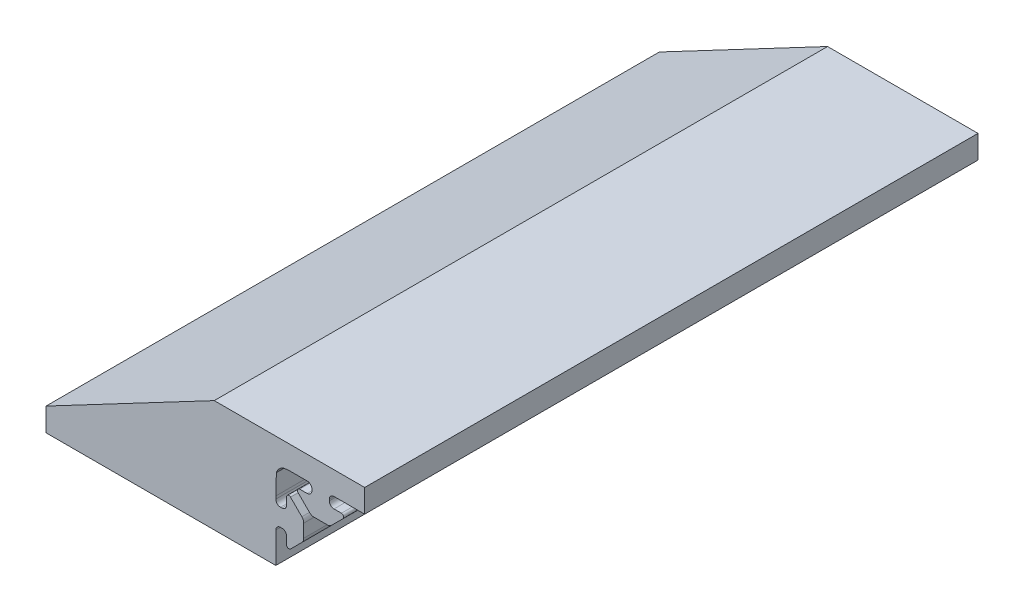
SolidWorks part; units mm, degrees
ref_plane "Front Plane" through (0, 0, 0) normal (0, 0, 1) x (1, 0, 0)
ref_plane "Top Plane" through (0, 0, 0) normal (0, 1, 0) x (1, 0, 0)
ref_plane "Right Plane" through (0, 0, 0) normal (1, 0, 0) x (0, 0, -1)
sketch "Sketch1" plane through (0, 0, 0) normal (0, 0, 1) x (1, 0, 0)
  line L6 (-87.85, -284.05) -> (-19.05, -284.05)
  line L7 (-19.05, -284.05) -> (-19.05, -269.05)
  line L8 (-19.05, -269.05) -> (-118.6495, -269.05)
  line L9 (-118.6495, -269.05) -> (-118.6495, -295.05)
  line L10 (-118.6495, -295.05) -> (-87.85, -295.05)
  line L11 (-87.85, -295.05) -> (-87.85, -284.05)
  line L12 (-87.85, -284.05) -> (-19.05, -284.05)
  line L13 (-19.05, -284.05) -> (-19.05, -269.05)
  line L14 (-19.05, -269.05) -> (-118.6495, -269.05)
  line L15 (-118.6495, -269.05) -> (-118.6495, -295.05)
  line L16 (-118.6495, -295.05) -> (-87.85, -295.05)
  line L17 (-87.85, -295.05) -> (-87.85, -284.05)
  line L44 (19.05, -6.9643) -> (19.05, -5.7912)
  line L45 (17.3228, -4.064) -> (16.7132, -4.064)
  line L46 (14.986, -5.7912) -> (14.986, -8.9963)
  line L47 (12.7826, -9.909) -> (7.8889, -5.0152)
  line L48 (6.985, -2.833) -> (6.985, 2.833)
  line L49 (7.8889, 5.0152) -> (12.7826, 9.909)
  line L50 (14.986, 8.9963) -> (14.986, 5.7912)
  line L51 (16.7132, 4.064) -> (17.3228, 4.064)
  line L52 (19.05, 5.7912) -> (19.05, 6.9643)
  line L53 (19.05, 8.9963) -> (19.05, 13.7235)
  line L54 (13.7235, 19.05) -> (8.9963, 19.05)
  line L55 (6.9643, 19.05) -> (5.7912, 19.05)
  line L56 (4.064, 17.3228) -> (4.064, 16.7132)
  line L57 (5.7912, 14.986) -> (8.9963, 14.986)
  line L58 (9.909, 12.7826) -> (5.0152, 7.8889)
  line L59 (2.833, 6.985) -> (-2.833, 6.985)
  line L60 (-5.0152, 7.8889) -> (-9.909, 12.7826)
  line L61 (-8.9963, 14.986) -> (-5.7912, 14.986)
  line L62 (-4.064, 16.7132) -> (-4.064, 17.3228)
  line L63 (-5.7912, 19.05) -> (-6.9643, 19.05)
  line L64 (-8.9963, 19.05) -> (-13.7235, 19.05)
  line L65 (-19.05, 13.7235) -> (-19.05, 8.9963)
  line L66 (-19.05, 6.9643) -> (-19.05, 5.7912)
  line L67 (-17.3228, 4.064) -> (-16.7132, 4.064)
  line L68 (-14.986, 5.7912) -> (-14.986, 8.9963)
  line L69 (-12.7826, 9.909) -> (-7.8889, 5.0152)
  line L70 (-6.985, 2.833) -> (-6.985, -2.833)
  line L71 (-7.8889, -5.0152) -> (-12.7826, -9.909)
  line L72 (-14.986, -8.9963) -> (-14.986, -5.7912)
  line L73 (-16.7132, -4.064) -> (-17.3228, -4.064)
  line L74 (-19.05, -5.7912) -> (-19.05, -6.9643)
  line L75 (-19.05, -8.9963) -> (-19.05, -13.7235)
  line L76 (-13.7235, -19.05) -> (-8.9963, -19.05)
  line L77 (-6.9643, -19.05) -> (-5.7912, -19.05)
  line L78 (-4.064, -17.3228) -> (-4.064, -16.7132)
  line L79 (-5.7912, -14.986) -> (-8.9963, -14.986)
  line L80 (-9.909, -12.7826) -> (-5.0152, -7.8889)
  line L81 (-2.833, -6.985) -> (2.833, -6.985)
  line L82 (5.0152, -7.8889) -> (9.909, -12.7826)
  line L83 (8.9963, -14.986) -> (5.7912, -14.986)
  line L84 (4.064, -16.7132) -> (4.064, -17.3228)
  line L85 (5.7912, -19.05) -> (6.9643, -19.05)
  line L86 (8.9963, -19.05) -> (13.7235, -19.05)
  line L87 (19.05, -13.7235) -> (19.05, -8.9963)
  line L88 (19.05, -6.9643) -> (19.05, -5.7912)
  line L89 (17.3228, -4.064) -> (16.7132, -4.064)
  line L90 (14.986, -5.7912) -> (14.986, -8.9963)
  line L91 (12.7826, -9.909) -> (7.8889, -5.0152)
  line L92 (6.985, -2.833) -> (6.985, 2.833)
  line L93 (7.8889, 5.0152) -> (12.7826, 9.909)
  line L94 (14.986, 8.9963) -> (14.986, 5.7912)
  line L95 (16.7132, 4.064) -> (17.3228, 4.064)
  line L96 (19.05, 5.7912) -> (19.05, 6.9643)
  line L97 (19.05, 8.9963) -> (19.05, 13.7235)
  line L98 (13.7235, 19.05) -> (8.9963, 19.05)
  line L99 (6.9643, 19.05) -> (5.7912, 19.05)
  line L100 (4.064, 17.3228) -> (4.064, 16.7132)
  line L101 (5.7912, 14.986) -> (8.9963, 14.986)
  line L102 (9.909, 12.7826) -> (5.0152, 7.8889)
  line L103 (2.833, 6.985) -> (-2.833, 6.985)
  line L104 (-5.0152, 7.8889) -> (-9.909, 12.7826)
  line L105 (-8.9963, 14.986) -> (-5.7912, 14.986)
  line L106 (-4.064, 16.7132) -> (-4.064, 17.3228)
  line L107 (-5.7912, 19.05) -> (-6.9643, 19.05)
  line L108 (-8.9963, 19.05) -> (-13.7235, 19.05)
  line L109 (-19.05, 13.7235) -> (-19.05, 8.9963)
  line L110 (-19.05, 6.9643) -> (-19.05, 5.7912)
  line L111 (-17.3228, 4.064) -> (-16.7132, 4.064)
  line L112 (-14.986, 5.7912) -> (-14.986, 8.9963)
  line L113 (-12.7826, 9.909) -> (-7.8889, 5.0152)
  line L114 (-6.985, 2.833) -> (-6.985, -2.833)
  line L115 (-7.8889, -5.0152) -> (-12.7826, -9.909)
  line L116 (-14.986, -8.9963) -> (-14.986, -5.7912)
  line L117 (-16.7132, -4.064) -> (-17.3228, -4.064)
  line L118 (-19.05, -5.7912) -> (-19.05, -6.9643)
  line L119 (-19.05, -8.9963) -> (-19.05, -13.7235)
  line L120 (-13.7235, -19.05) -> (-8.9963, -19.05)
  line L121 (-6.9643, -19.05) -> (-5.7912, -19.05)
  line L122 (-4.064, -17.3228) -> (-4.064, -16.7132)
  line L123 (-5.7912, -14.986) -> (-8.9963, -14.986)
  line L124 (-9.909, -12.7826) -> (-5.0152, -7.8889)
  line L125 (-2.833, -6.985) -> (2.833, -6.985)
  line L126 (5.0152, -7.8889) -> (9.909, -12.7826)
  line L127 (8.9963, -14.986) -> (5.7912, -14.986)
  line L128 (4.064, -16.7132) -> (4.064, -17.3228)
  line L129 (5.7912, -19.05) -> (6.9643, -19.05)
  line L130 (8.9963, -19.05) -> (13.7235, -19.05)
  line L131 (19.05, -13.7235) -> (19.05, -8.9963)
  arc A52 (19.05, -6.9643) -> (19.05, -8.9963) centre (19.05, -7.9803) ccw
  arc A53 (19.05, -5.7912) -> (17.3228, -4.064) centre (17.3228, -5.7912) ccw
  arc A54 (16.7132, -4.064) -> (14.986, -5.7912) centre (16.7132, -5.7912) ccw
  arc A55 (12.7826, -9.909) -> (14.986, -8.9963) centre (13.6953, -8.9963) ccw
  arc A56 (6.985, -2.833) -> (7.8889, -5.0152) centre (10.0711, -2.833) ccw
  arc A57 (7.8889, 5.0152) -> (6.985, 2.833) centre (10.0711, 2.833) ccw
  arc A58 (14.986, 8.9963) -> (12.7826, 9.909) centre (13.6953, 8.9963) ccw
  arc A59 (14.986, 5.7912) -> (16.7132, 4.064) centre (16.7132, 5.7912) ccw
  arc A60 (17.3228, 4.064) -> (19.05, 5.7912) centre (17.3228, 5.7912) ccw
  arc A61 (19.05, 8.9963) -> (19.05, 6.9643) centre (19.05, 7.9803) ccw
  arc A62 (18.8293, 15.7312) -> (19.05, 13.7235) centre (19.05, 14.7395) ccw
  arc A63 (18.8293, 15.7312) -> (15.7312, 18.8293) centre (14.3002, 14.3002) ccw
  arc A64 (13.7235, 19.05) -> (15.7312, 18.8293) centre (14.7395, 19.05) ccw
  arc A65 (6.9643, 19.05) -> (8.9963, 19.05) centre (7.9803, 19.05) ccw
  arc A66 (5.7912, 19.05) -> (4.064, 17.3228) centre (5.7912, 17.3228) ccw
  arc A67 (4.064, 16.7132) -> (5.7912, 14.986) centre (5.7912, 16.7132) ccw
  arc A68 (9.909, 12.7826) -> (8.9963, 14.986) centre (8.9963, 13.6953) ccw
  arc A69 (2.833, 6.985) -> (5.0152, 7.8889) centre (2.833, 10.0711) ccw
  arc A70 (-5.0152, 7.8889) -> (-2.833, 6.985) centre (-2.833, 10.0711) ccw
  arc A71 (-8.9963, 14.986) -> (-9.909, 12.7826) centre (-8.9963, 13.6953) ccw
  arc A72 (-5.7912, 14.986) -> (-4.064, 16.7132) centre (-5.7912, 16.7132) ccw
  arc A73 (-4.064, 17.3228) -> (-5.7912, 19.05) centre (-5.7912, 17.3228) ccw
  arc A74 (-8.9963, 19.05) -> (-6.9643, 19.05) centre (-7.9803, 19.05) ccw
  arc A75 (-15.7312, 18.8293) -> (-13.7235, 19.05) centre (-14.7395, 19.05) ccw
  arc A76 (-15.7312, 18.8293) -> (-18.8293, 15.7312) centre (-14.3002, 14.3002) ccw
  arc A77 (-19.05, 13.7235) -> (-18.8293, 15.7312) centre (-19.05, 14.7395) ccw
  arc A78 (-19.05, 6.9643) -> (-19.05, 8.9963) centre (-19.05, 7.9803) ccw
  arc A79 (-19.05, 5.7912) -> (-17.3228, 4.064) centre (-17.3228, 5.7912) ccw
  arc A80 (-16.7132, 4.064) -> (-14.986, 5.7912) centre (-16.7132, 5.7912) ccw
  arc A81 (-12.7826, 9.909) -> (-14.986, 8.9963) centre (-13.6953, 8.9963) ccw
  arc A82 (-6.985, 2.833) -> (-7.8889, 5.0152) centre (-10.0711, 2.833) ccw
  arc A83 (-7.8889, -5.0152) -> (-6.985, -2.833) centre (-10.0711, -2.833) ccw
  arc A84 (-14.986, -8.9963) -> (-12.7826, -9.909) centre (-13.6953, -8.9963) ccw
  arc A85 (-14.986, -5.7912) -> (-16.7132, -4.064) centre (-16.7132, -5.7912) ccw
  arc A86 (-17.3228, -4.064) -> (-19.05, -5.7912) centre (-17.3228, -5.7912) ccw
  arc A87 (-19.05, -8.9963) -> (-19.05, -6.9643) centre (-19.05, -7.9803) ccw
  arc A88 (-18.8293, -15.7312) -> (-19.05, -13.7235) centre (-19.05, -14.7395) ccw
  arc A89 (-18.8293, -15.7312) -> (-15.7312, -18.8293) centre (-14.3002, -14.3002) ccw
  arc A90 (-13.7235, -19.05) -> (-15.7312, -18.8293) centre (-14.7395, -19.05) ccw
  arc A91 (-6.9643, -19.05) -> (-8.9963, -19.05) centre (-7.9803, -19.05) ccw
  arc A92 (-5.7912, -19.05) -> (-4.064, -17.3228) centre (-5.7912, -17.3228) ccw
  arc A93 (-4.064, -16.7132) -> (-5.7912, -14.986) centre (-5.7912, -16.7132) ccw
  arc A94 (-9.909, -12.7826) -> (-8.9963, -14.986) centre (-8.9963, -13.6953) ccw
  arc A95 (-2.833, -6.985) -> (-5.0152, -7.8889) centre (-2.833, -10.0711) ccw
  arc A96 (5.0152, -7.8889) -> (2.833, -6.985) centre (2.833, -10.0711) ccw
  arc A97 (8.9963, -14.986) -> (9.909, -12.7826) centre (8.9963, -13.6953) ccw
  arc A98 (5.7912, -14.986) -> (4.064, -16.7132) centre (5.7912, -16.7132) ccw
  arc A99 (4.064, -17.3228) -> (5.7912, -19.05) centre (5.7912, -17.3228) ccw
  arc A100 (8.9963, -19.05) -> (6.9643, -19.05) centre (7.9803, -19.05) ccw
  arc A101 (15.7312, -18.8293) -> (13.7235, -19.05) centre (14.7395, -19.05) ccw
  arc A102 (15.7312, -18.8293) -> (18.8293, -15.7312) centre (14.3002, -14.3002) ccw
  arc A103 (19.05, -13.7235) -> (18.8293, -15.7312) centre (19.05, -14.7395) ccw
  arc A104 (19.05, -6.9643) -> (19.05, -8.9963) centre (19.05, -7.9803) ccw
  arc A105 (19.05, -5.7912) -> (17.3228, -4.064) centre (17.3228, -5.7912) ccw
  arc A106 (16.7132, -4.064) -> (14.986, -5.7912) centre (16.7132, -5.7912) ccw
  arc A107 (12.7826, -9.909) -> (14.986, -8.9963) centre (13.6953, -8.9963) ccw
  arc A108 (6.985, -2.833) -> (7.8889, -5.0152) centre (10.0711, -2.833) ccw
  arc A109 (7.8889, 5.0152) -> (6.985, 2.833) centre (10.0711, 2.833) ccw
  arc A110 (14.986, 8.9963) -> (12.7826, 9.909) centre (13.6953, 8.9963) ccw
  arc A111 (14.986, 5.7912) -> (16.7132, 4.064) centre (16.7132, 5.7912) ccw
  arc A112 (17.3228, 4.064) -> (19.05, 5.7912) centre (17.3228, 5.7912) ccw
  arc A113 (19.05, 8.9963) -> (19.05, 6.9643) centre (19.05, 7.9803) ccw
  arc A114 (18.8293, 15.7312) -> (19.05, 13.7235) centre (19.05, 14.7395) ccw
  arc A115 (18.8293, 15.7312) -> (15.7312, 18.8293) centre (14.3002, 14.3002) ccw
  arc A116 (13.7235, 19.05) -> (15.7312, 18.8293) centre (14.7395, 19.05) ccw
  arc A117 (6.9643, 19.05) -> (8.9963, 19.05) centre (7.9803, 19.05) ccw
  arc A118 (5.7912, 19.05) -> (4.064, 17.3228) centre (5.7912, 17.3228) ccw
  arc A119 (4.064, 16.7132) -> (5.7912, 14.986) centre (5.7912, 16.7132) ccw
  arc A120 (9.909, 12.7826) -> (8.9963, 14.986) centre (8.9963, 13.6953) ccw
  arc A121 (2.833, 6.985) -> (5.0152, 7.8889) centre (2.833, 10.0711) ccw
  arc A122 (-5.0152, 7.8889) -> (-2.833, 6.985) centre (-2.833, 10.0711) ccw
  arc A123 (-8.9963, 14.986) -> (-9.909, 12.7826) centre (-8.9963, 13.6953) ccw
  arc A124 (-5.7912, 14.986) -> (-4.064, 16.7132) centre (-5.7912, 16.7132) ccw
  arc A125 (-4.064, 17.3228) -> (-5.7912, 19.05) centre (-5.7912, 17.3228) ccw
  arc A126 (-8.9963, 19.05) -> (-6.9643, 19.05) centre (-7.9803, 19.05) ccw
  arc A127 (-15.7312, 18.8293) -> (-13.7235, 19.05) centre (-14.7395, 19.05) ccw
  arc A128 (-15.7312, 18.8293) -> (-18.8293, 15.7312) centre (-14.3002, 14.3002) ccw
  arc A129 (-19.05, 13.7235) -> (-18.8293, 15.7312) centre (-19.05, 14.7395) ccw
  arc A130 (-19.05, 6.9643) -> (-19.05, 8.9963) centre (-19.05, 7.9803) ccw
  arc A131 (-19.05, 5.7912) -> (-17.3228, 4.064) centre (-17.3228, 5.7912) ccw
  arc A132 (-16.7132, 4.064) -> (-14.986, 5.7912) centre (-16.7132, 5.7912) ccw
  arc A133 (-12.7826, 9.909) -> (-14.986, 8.9963) centre (-13.6953, 8.9963) ccw
  arc A134 (-6.985, 2.833) -> (-7.8889, 5.0152) centre (-10.0711, 2.833) ccw
  arc A135 (-7.8889, -5.0152) -> (-6.985, -2.833) centre (-10.0711, -2.833) ccw
  arc A136 (-14.986, -8.9963) -> (-12.7826, -9.909) centre (-13.6953, -8.9963) ccw
  arc A137 (-14.986, -5.7912) -> (-16.7132, -4.064) centre (-16.7132, -5.7912) ccw
  arc A138 (-17.3228, -4.064) -> (-19.05, -5.7912) centre (-17.3228, -5.7912) ccw
  arc A139 (-19.05, -8.9963) -> (-19.05, -6.9643) centre (-19.05, -7.9803) ccw
  arc A140 (-18.8293, -15.7312) -> (-19.05, -13.7235) centre (-19.05, -14.7395) ccw
  arc A141 (-18.8293, -15.7312) -> (-15.7312, -18.8293) centre (-14.3002, -14.3002) ccw
  arc A142 (-13.7235, -19.05) -> (-15.7312, -18.8293) centre (-14.7395, -19.05) ccw
  arc A143 (-6.9643, -19.05) -> (-8.9963, -19.05) centre (-7.9803, -19.05) ccw
  arc A144 (-5.7912, -19.05) -> (-4.064, -17.3228) centre (-5.7912, -17.3228) ccw
  arc A145 (-4.064, -16.7132) -> (-5.7912, -14.986) centre (-5.7912, -16.7132) ccw
  arc A146 (-9.909, -12.7826) -> (-8.9963, -14.986) centre (-8.9963, -13.6953) ccw
  arc A147 (-2.833, -6.985) -> (-5.0152, -7.8889) centre (-2.833, -10.0711) ccw
  arc A148 (5.0152, -7.8889) -> (2.833, -6.985) centre (2.833, -10.0711) ccw
  arc A149 (8.9963, -14.986) -> (9.909, -12.7826) centre (8.9963, -13.6953) ccw
  arc A150 (5.7912, -14.986) -> (4.064, -16.7132) centre (5.7912, -16.7132) ccw
  arc A151 (4.064, -17.3228) -> (5.7912, -19.05) centre (5.7912, -17.3228) ccw
  arc A152 (8.9963, -19.05) -> (6.9643, -19.05) centre (7.9803, -19.05) ccw
  arc A153 (15.7312, -18.8293) -> (13.7235, -19.05) centre (14.7395, -19.05) ccw
  arc A154 (15.7312, -18.8293) -> (18.8293, -15.7312) centre (14.3002, -14.3002) ccw
  arc A155 (19.05, -13.7235) -> (18.8293, -15.7312) centre (19.05, -14.7395) ccw
  dimension "D1" = 0
  dimension "D2" = 0
sketch "Sketch2" plane through (0, 0, 0) normal (0, 0, 1) x (1, 0, 0)
  line L60 (-7.285, 2.833) -> (-7.285, -2.833)
  line L61 (-8.101, -4.8031) -> (-12.9948, -9.6968)
  line L62 (-14.686, -8.9963) -> (-14.686, -5.7912)
  line L63 (-16.7132, -3.764) -> (-17.3228, -3.764)
  line L64 (-17.3228, 3.764) -> (-16.7132, 3.764)
  line L65 (-14.686, 5.7912) -> (-14.686, 8.9963)
  line L66 (-12.9948, 9.6968) -> (-8.101, 4.8031)
  line L67 (-7.285, 2.833) -> (-7.285, -2.833)
  line L68 (-8.101, -4.8031) -> (-12.9948, -9.6968)
  line L69 (-14.686, -8.9963) -> (-14.686, -5.7912)
  line L70 (-16.7132, -3.764) -> (-17.3228, -3.764)
  line L71 (-17.3228, 3.764) -> (-16.7132, 3.764)
  line L72 (-14.686, 5.7912) -> (-14.686, 8.9963)
  line L73 (-12.9948, 9.6968) -> (-8.101, 4.8031)
  line L75 (-8.9963, 14.686) -> (-5.7912, 14.686)
  line L76 (-3.764, 16.7132) -> (-3.764, 17.3228)
  line L77 (-8.9963, 14.686) -> (-5.7912, 14.686)
  line L78 (-3.764, 16.7132) -> (-3.764, 17.3228)
  line L119 (6.9643, 19.35) -> (5.7912, 19.35)
  line L120 (3.764, 17.3228) -> (3.764, 16.7132)
  line L121 (5.7912, 14.686) -> (8.9963, 14.686)
  line L122 (9.6968, 12.9948) -> (4.8031, 8.101)
  line L123 (2.833, 7.285) -> (-2.833, 7.285)
  line L124 (-4.8031, 8.101) -> (-9.6968, 12.9948)
  line L125 (6.9643, 19.35) -> (5.7912, 19.35)
  line L126 (3.764, 17.3228) -> (3.764, 16.7132)
  line L127 (5.7912, 14.686) -> (8.9963, 14.686)
  line L128 (9.6968, 12.9948) -> (4.8031, 8.101)
  line L129 (2.833, 7.285) -> (-2.833, 7.285)
  line L130 (-4.8031, 8.101) -> (-9.6968, 12.9948)
  line L132 (-19.35, 6.9643) -> (-19.35, 5.7912)
  line L133 (-19.35, 6.9643) -> (-19.35, 5.7912)
  line L135 (-8.9963, 19.35) -> (-13.7235, 19.35)
  line L136 (-8.9963, 19.35) -> (-13.7235, 19.35)
  line L137 (-19.35, -6.9643) -> (-19.35, -19.05)
  line L138 (-19.35, -5.7912) -> (-19.35, -6.9643)
  line L139 (-19.35, -5.7912) -> (-19.35, -6.9643)
  line L140 (-19.35, 6.9643) -> (-19.1154, 15.8216)
  line L142 (-15.8216, 19.1154) -> (-13.7235, 19.35)
  line L143 (-5.7912, 19.35) -> (-6.9643, 19.35)
  line L144 (-5.7912, 19.35) -> (-6.9643, 19.35)
  line L145 (-8.9963, 19.35) -> (-6.9643, 19.35)
  line L146 (-118.6495, -19.05) -> (-118.6495, -9.05)
  line L147 (19.05, 19.35) -> (6.9643, 19.35)
  line L148 (-19.35, -19.05) -> (-118.6495, -19.05)
  line L149 (19.05, 19.35) -> (19.05, 29.35)
  line L150 (19.05, 29.35) -> (-45.95, 29.35)
  line L151 (-118.6495, -19.05) -> (-118.6495, -9.05)
  line L152 (-118.6495, -9.05) -> (-45.95, 29.35)
  arc A44 (-7.285, 2.833) -> (-8.101, 4.8031) centre (-10.0711, 2.833) ccw
  arc A45 (-8.101, -4.8031) -> (-7.285, -2.833) centre (-10.0711, -2.833) ccw
  arc A46 (-14.686, -8.9963) -> (-12.9948, -9.6968) centre (-13.6953, -8.9963) ccw
  arc A47 (-14.686, -5.7912) -> (-16.7132, -3.764) centre (-16.7132, -5.7912) ccw
  arc A48 (-16.7132, 3.764) -> (-14.686, 5.7912) centre (-16.7132, 5.7912) ccw
  arc A49 (-12.9948, 9.6968) -> (-14.686, 8.9963) centre (-13.6953, 8.9963) ccw
  arc A50 (-7.285, 2.833) -> (-8.101, 4.8031) centre (-10.0711, 2.833) ccw
  arc A51 (-8.101, -4.8031) -> (-7.285, -2.833) centre (-10.0711, -2.833) ccw
  arc A52 (-14.686, -8.9963) -> (-12.9948, -9.6968) centre (-13.6953, -8.9963) ccw
  arc A53 (-14.686, -5.7912) -> (-16.7132, -3.764) centre (-16.7132, -5.7912) ccw
  arc A54 (-16.7132, 3.764) -> (-14.686, 5.7912) centre (-16.7132, 5.7912) ccw
  arc A55 (-12.9948, 9.6968) -> (-14.686, 8.9963) centre (-13.6953, 8.9963) ccw
  arc A56 (-8.9963, 14.686) -> (-9.6968, 12.9948) centre (-8.9963, 13.6953) ccw
  arc A57 (-5.7912, 14.686) -> (-3.764, 16.7132) centre (-5.7912, 16.7132) ccw
  arc A58 (-8.9963, 14.686) -> (-9.6968, 12.9948) centre (-8.9963, 13.6953) ccw
  arc A59 (-5.7912, 14.686) -> (-3.764, 16.7132) centre (-5.7912, 16.7132) ccw
  arc A93 (5.7912, 19.35) -> (3.764, 17.3228) centre (5.7912, 17.3228) ccw
  arc A94 (3.764, 16.7132) -> (5.7912, 14.686) centre (5.7912, 16.7132) ccw
  arc A95 (9.6968, 12.9948) -> (8.9963, 14.686) centre (8.9963, 13.6953) ccw
  arc A96 (2.833, 7.285) -> (4.8031, 8.101) centre (2.833, 10.0711) ccw
  arc A97 (-4.8031, 8.101) -> (-2.833, 7.285) centre (-2.833, 10.0711) ccw
  arc A98 (5.7912, 19.35) -> (3.764, 17.3228) centre (5.7912, 17.3228) ccw
  arc A99 (3.764, 16.7132) -> (5.7912, 14.686) centre (5.7912, 16.7132) ccw
  arc A100 (9.6968, 12.9948) -> (8.9963, 14.686) centre (8.9963, 13.6953) ccw
  arc A101 (2.833, 7.285) -> (4.8031, 8.101) centre (2.833, 10.0711) ccw
  arc A102 (-4.8031, 8.101) -> (-2.833, 7.285) centre (-2.833, 10.0711) ccw
  arc A104 (-19.35, 5.7912) -> (-17.3228, 3.764) centre (-17.3228, 5.7912) ccw
  arc A105 (-19.35, 5.7912) -> (-17.3228, 3.764) centre (-17.3228, 5.7912) ccw
  arc A107 (-15.8216, 19.1154) -> (-19.1154, 15.8216) centre (-14.3002, 14.3002) ccw
  arc A108 (-15.8216, 19.1154) -> (-19.1154, 15.8216) centre (-14.3002, 14.3002) ccw
  arc A111 (-17.3228, -3.764) -> (-19.35, -5.7912) centre (-17.3228, -5.7912) ccw
  arc A112 (-17.3228, -3.764) -> (-19.35, -5.7912) centre (-17.3228, -5.7912) ccw
  arc A115 (-3.764, 17.3228) -> (-5.7912, 19.35) centre (-5.7912, 17.3228) ccw
  arc A116 (-3.764, 17.3228) -> (-5.7912, 19.35) centre (-5.7912, 17.3228) ccw
  dimension "D8" = 0.3
  dimension "D1" = 0.3
  dimension "D2" = 0.3
  dimension "D3" = 0.3
  dimension "D4" = 0.3
  dimension "D5" = 0.3
  dimension "D6" = 0.3
  dimension "D7" = 0.3
extrude "Boss-Extrude1" add sketch "Sketch2" against normal blind 265 contours A116 L78 A59 L77 A58 L130 A102 L129 A101 L128 A100 L127 A99 L126 A98 L125 L147 L149 L150 L152 L146 L148 L137 L139 A112 L70 A53 L69 A52 L68 A51 L67 A50 L73 A55 L72 A54 L71 A105 L133 L140 A108 L142 L136 L145 L144
sketch "Sketch3" plane through (-118.6495, 0, 0) normal (-1, 0, 0) x (0, 0, 1)
  circle A0 centre (-10, -14.05) radius 1.65
  circle A1 centre (-275.03, -14.05) radius 1.65
  circle A2 centre (-142.515, -14.05) radius 1.65
extrude "Cut-Extrude1" cut sketch "Sketch3" against normal blind 40
